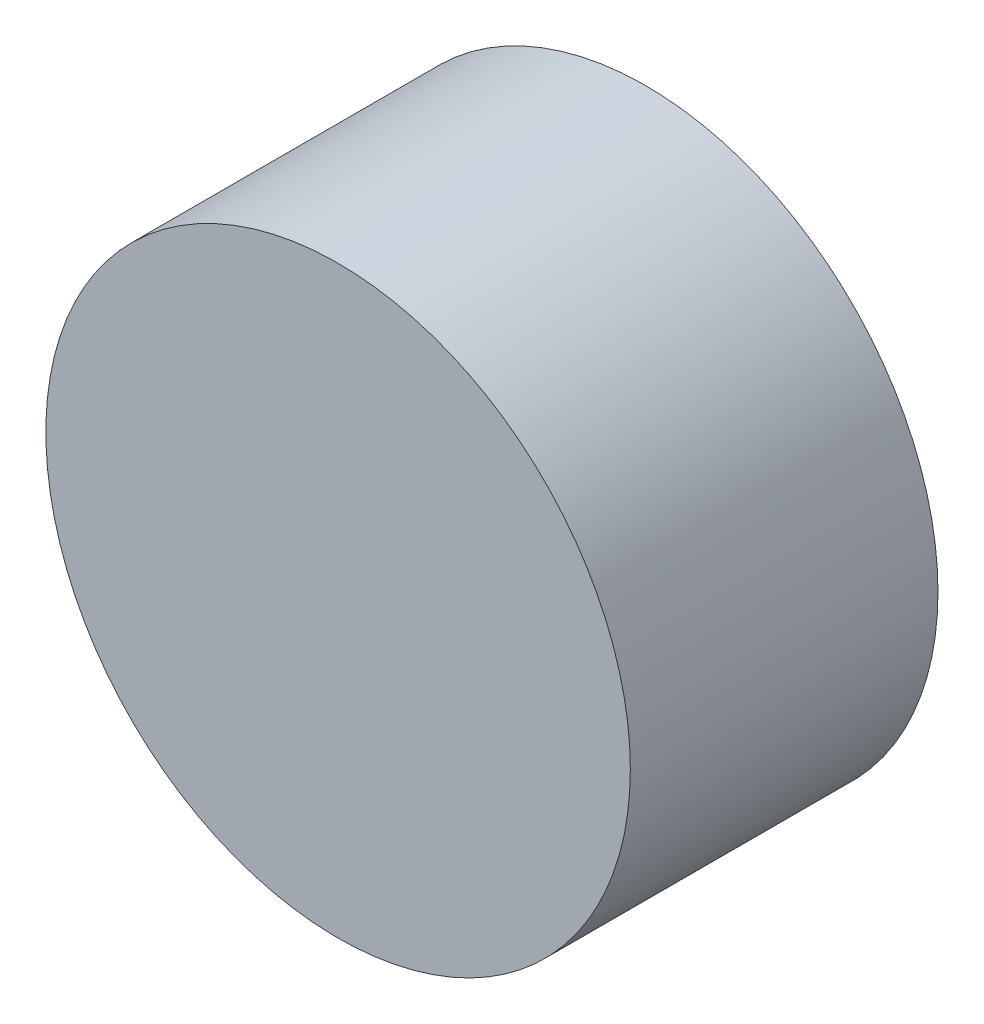
SolidWorks part; units mm, degrees
ref_plane "Front Plane" through (0, 0, 0) normal (0, 0, 1) x (1, 0, 0)
ref_plane "Top Plane" through (0, 0, 0) normal (0, 1, 0) x (1, 0, 0)
ref_plane "Right Plane" through (0, 0, 0) normal (1, 0, 0) x (0, 0, -1)
sketch "Sketch1" plane through (0, 0, 0) normal (0, 0, 1) x (1, 0, 0)
  circle A0 centre (0, 0) radius 57
extrude "Boss-Extrude1" add sketch "Sketch1" along normal blind 60 contours A0
